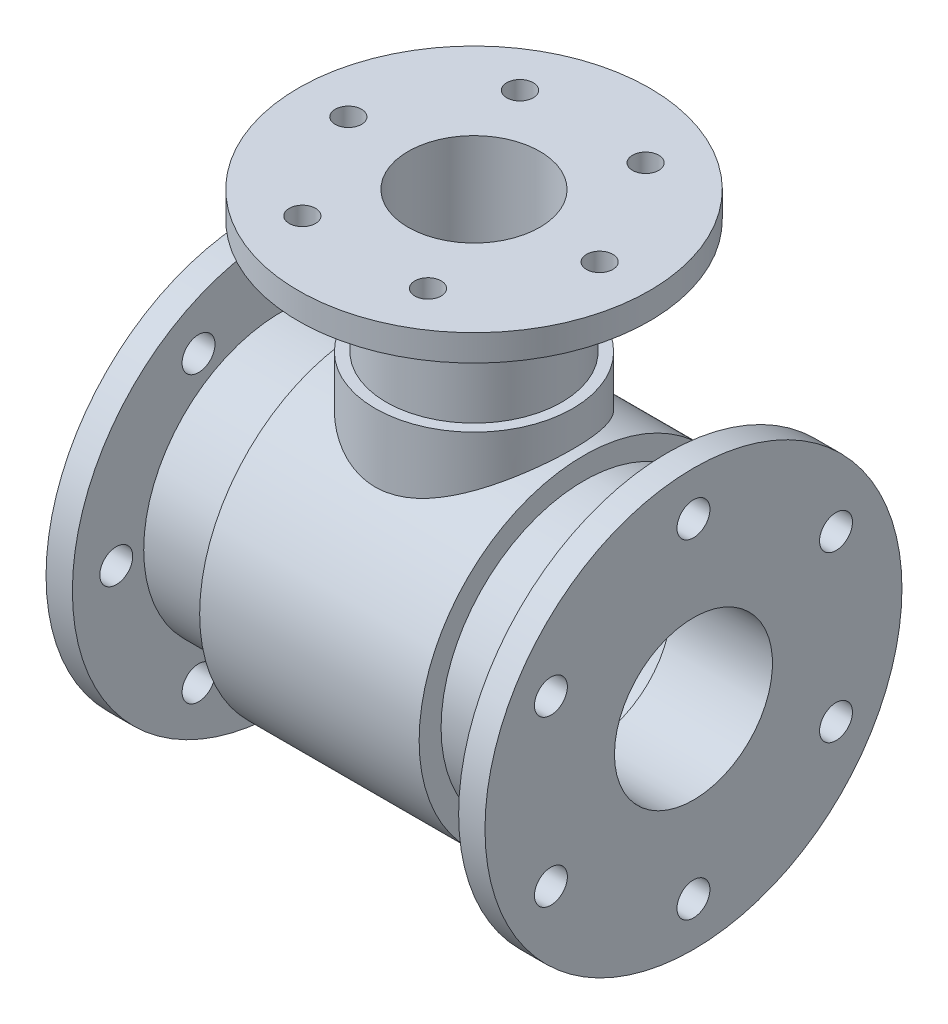
SolidWorks part; units mm, degrees
ref_plane "Front Plane" through (0, 0, 0) normal (0, 0, 1) x (1, 0, 0)
ref_plane "Top Plane" through (0, 0, 0) normal (0, 1, 0) x (1, 0, 0)
ref_plane "Right Plane" through (0, 0, 0) normal (1, 0, 0) x (0, 0, -1)
sketch "Sketch1" plane through (0, 0, 0) normal (0, 0, 1) x (1, 0, 0)
  line L0 (-100, -52.5) -> (-100, -95)
  line L1 (-100, -95) -> (-88, -95)
  line L2 (-88, -95) -> (-88, -62.5)
  line L3 (-88, -62.5) -> (-50, -62.5)
  line L4 (-50, -62.5) -> (-50, -75)
  line L5 (-50, -75) -> (50, -75)
  line L6 (50, -75) -> (50, -65)
  line L7 (50, -65) -> (74, -65)
  line L8 (74, -65) -> (74, -50)
  line L9 (74, -50) -> (88, -50)
  line L10 (88, -50) -> (88, -95)
  line L11 (88, -95) -> (100, -95)
  line L12 (100, -95) -> (100, -36)
  line L13 (100, -36) -> (54, -36)
  line L14 (54, -36) -> (54, -43.5)
  line L15 (54, -43.5) -> (37, -43.5)
  line L16 (37, -43.5) -> (37, -52.5)
  line L17 (37, -52.5) -> (-35, -52.5)
  line L18 (-35, -52.5) -> (-35, -47.5)
  line L19 (-35, -47.5) -> (-95, -47.5)
  line L20 (-95, -47.5) -> (-95, -52.5)
  line L21 (-95, -52.5) -> (-100, -52.5)
  line L22 (0, -1.9531) -> (0, -96492.4496) construction
  line L23 (0, 0) -> (96490.4964, 0) construction
  point P27 (74, -57.5)
  point P28 (50, -70)
  point P29 (81, -50)
  point P30 (45.5, -43.5)
  dimension "D1" = 150
  dimension "D2" = 135
  dimension "D3" = 63
  dimension "D4" = 26
  dimension "D5" = 46
  dimension "D6" = 50
  dimension "D7" = 12
  dimension "D8" = 12
  dimension "D9" = 150
  dimension "D10" = 130
  dimension "D11" = 100
  dimension "D12" = 87
  dimension "D13" = 72
  dimension "D14" = 105
  dimension "D15" = 95
  dimension "D16" = 125
  dimension "D17" = 190
  dimension "D18" = 5
revolve "Revolve1" add sketch "Sketch1" angle 360 about L23
hole_wizard "Ø10.0mm Dowel Hole1" positions "Sketch2" profile "Sketch3" hole size "Ø10.0" standard "ANSI Metric"
sketch "Sketch2" plane through (100, 0, 0) normal (1, 0, 0) x (0, 0, -1)
  circle A2 centre (0, 0) radius 75 construction
  point P0 (0, 75)
  point P11 (0, 0)
  dimension "D1" = 150
sketch "Sketch3" plane through (100, 75, 0) normal (0, 1, 0) x (0, 0, -1)
  line L0 (0, 0) -> (0, 12)
  line L1 (0, 12) -> (7.5, 12)
  line L2 (7.5, 12) -> (7.5, 0)
  line L5 (7.5, 0) -> (0, 0)
  line L11 (0, -6.35) -> (0, 107.95) construction
  dimension "Thru Hole Dia." = 15
  dimension "Thru Hole Depth" = 12
pattern_circular "CirPattern1" count 6 over 360 about axis through (0, 0, 0) along (1, 0, 0) of "Ø10.0mm Dowel Hole1"
hole_wizard "Ø10.0mm Dowel Hole2" positions "Sketch4" profile "Sketch5" hole size "Ø10.0" standard "ANSI Metric"
sketch "Sketch4" plane through (-100, 0, 0) normal (-1, 0, 0) x (0, 0, 1)
  circle A0 centre (0, 0) radius 75 construction
  point P0 (75, 0)
  dimension "D1" = 150
sketch "Sketch5" plane through (-100, 0, 75) normal (0, 1, 0) x (0, 0, 1)
  line L0 (0, 0) -> (0, 12)
  line L1 (0, 12) -> (7.5, 12)
  line L2 (7.5, 12) -> (7.5, 0)
  line L5 (7.5, 0) -> (0, 0)
  line L11 (0, -6.35) -> (0, 107.95) construction
  dimension "Thru Hole Dia." = 15
  dimension "Thru Hole Depth" = 12
pattern_circular "CirPattern2" count 6 over 360 about axis through (0, 0, 0) along (1, 0, 0) of "Ø10.0mm Dowel Hole2"
sketch "Sketch7" plane through (0, 0, 0) normal (0, 0, 1) x (1, 0, 0)
  line L0 (0, 0) -> (0, 50000) construction
  line L1 (0, 155) -> (80, 155)
  line L2 (80, 155) -> (80, 143)
  line L3 (80, 143) -> (40, 143)
  line L4 (40, 143) -> (40, 91)
  line L5 (40, 91) -> (45, 91)
  line L6 (45, 91) -> (45, 75)
  line L7 (50, 75) -> (-50, 75) construction
  line L8 (0, 155) -> (0, 75)
  line L9 (45, 75) -> (0, 75)
  point P13 (42.5, 91)
  dimension "D1" = 12
  dimension "D2" = 64
  dimension "D3" = 80
  dimension "D4" = 80
  dimension "D5" = 90
  dimension "D6" = 160
revolve "Revolve3" add sketch "Sketch7" angle 360 about L0
sketch "Sketch12" plane through (0, 75, 0) normal (0, -1, 0) x (1, 0, 0)
  circle A1 centre (0, 0) radius 45
  circle A2 centre (0, 0) radius 45
  dimension "D1" = 0
extrude "Boss-Extrude1" add sketch "Sketch12" along normal up to surface up to face at (50, 0, 75)
hole_wizard "Ø10.0mm Dowel Hole3" positions "Sketch13" profile "Sketch15" hole size "Ø10.0" standard "ANSI Metric"
sketch "Sketch13" plane through (0, 155, 0) normal (0, 1, 0) x (1, 0, 0)
  point P0 (0, 0)
sketch "Sketch15" plane through (0, 155, 0) normal (1, 0, 0) x (0, 0, 1)
  line L0 (0, 0) -> (0, 202.5)
  line L1 (0, 202.5) -> (30, 202.5)
  line L2 (30, 202.5) -> (30, 0)
  line L5 (30, 0) -> (0, 0)
  line L10 (0, 202.5) -> (-30, 202.5) construction
  line L11 (0, -6.35) -> (0, 107.95) construction
  dimension "Hole Dia." = 60
  dimension "Hole Depth" = 202.5
  dimension "Drill Angle" = 180
hole_wizard "Ø12.0mm Dowel Hole1" positions "3DSketch1" profile "Sketch17" hole size "Ø12.0" standard "ANSI Metric"
sketch3d "3DSketch1"
  line L0 (-2.0605, 0, 0) -> (-50002.0605, 0, 0) construction
  point P0 (-57.2529, 155, 0)
  point P15 (0, 0, 0)
sketch "Sketch17" plane through (-57.2529, 155, 0) normal (1, 0, 0) x (0, 0, 1)
  line L0 (0, 0) -> (0, 12)
  line L1 (0, 12) -> (6, 12)
  line L2 (6, 12) -> (6, 0)
  line L5 (6, 0) -> (0, 0)
  line L11 (0, -6.35) -> (0, 107.95) construction
  dimension "Thru Hole Dia." = 12
  dimension "Thru Hole Depth" = 12
pattern_circular "CirPattern3" count 6 over 360 about axis through (0, 0, 0) along (0, 1, 0) of "Ø12.0mm Dowel Hole1"
